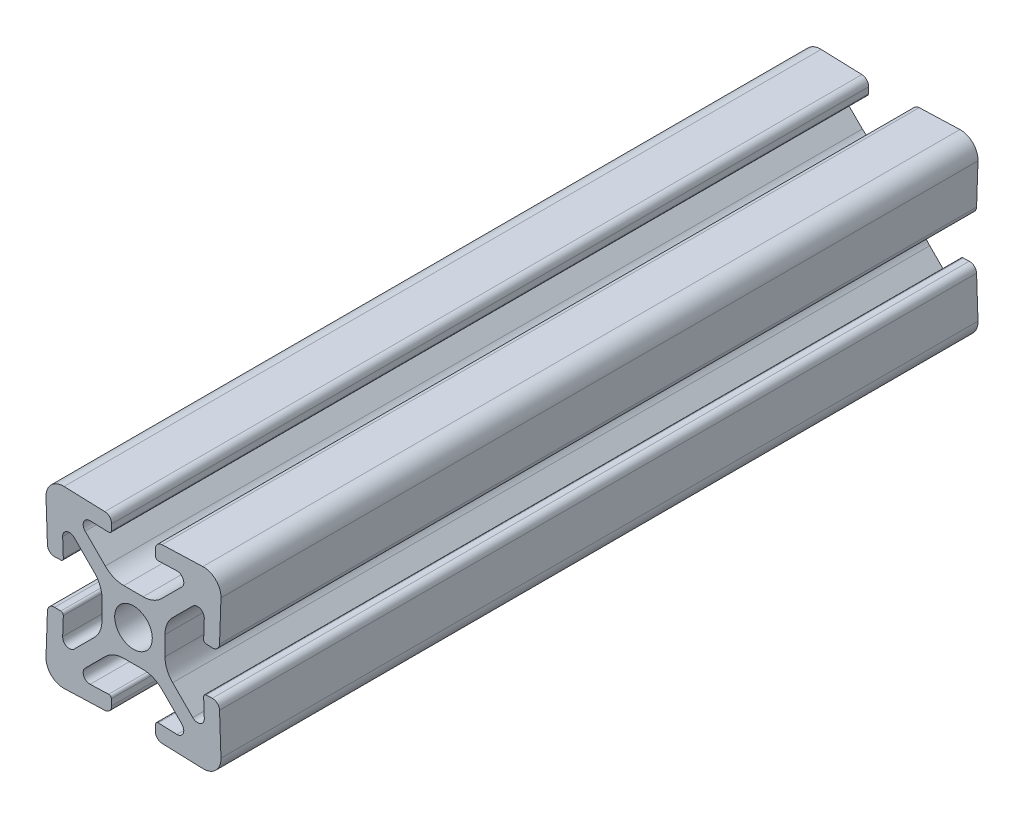
SolidWorks part; units mm, degrees
ref_plane "Front Plane" through (0, 0, 0) normal (0, 0, 1) x (1, 0, 0)
ref_plane "Top Plane" through (0, 0, 0) normal (0, 1, 0) x (1, 0, 0)
ref_plane "Right Plane" through (0, 0, 0) normal (1, 0, 0) x (0, 0, -1)
sketch "Sketch1" plane through (0, 0, 0) normal (0, 0, 1) x (1, 0, 0)
  line L0 (0, 0) -> (0, 10) construction
  line L1 (0, 0) -> (10, 0) construction
  line L2 (0, 0) -> (-10, 10) construction
  line L3 (-7.9302, 9.9988) -> (-3.2721, 9.8361)
  line L4 (-10, 10) -> (0, 10) construction
  line L6 (-2.8352, 8.0198) -> (-4.953, 8.0937)
  line L10 (0, 3.6) -> (-1.1022, 3.6)
  line L11 (-3.2236, 4.4787) -> (-5.5244, 6.7796)
  line L24 (0, 0) -> (-10, 0) construction
  line L25 (-10, 0) -> (0, 0) construction
  line L26 (0, 0) -> (0, -10) construction
  line L27 (-10, -10) -> (-10, 10) construction
  line L28 (0, 10) -> (10, 10) construction
  line L29 (-2.5249, 8.3091) -> (-2.5005, 9.0087)
  line L30 (-10, -10) -> (10, -10) construction
  arc A0 (-9.4142, 9.4142) -> (-7.9302, 9.9988) centre (-8, 8) cw
  arc A5 (-3.2721, 9.8361) -> (-2.5005, 9.0087) centre (-3.3, 9.0366) cw
  arc A6 (-1.1022, 3.6) -> (-3.2236, 4.4787) centre (-1.1022, 6.6) cw
  circle A16 centre (0, 0) radius 2.15
  arc A18 (-5.5244, 6.7796) -> (-4.953, 8.0937) centre (-4.9799, 7.3241) cw
  arc A20 (-2.8352, 8.0198) -> (-2.5249, 8.3091) centre (-2.8247, 8.3196) ccw
  point P15 (0, 0)
  point P42 (-2.3449, 3.6)
  point P80 (-10, 0)
  point P85 (0, -10)
  point P88 (0, -10)
  dimension "D11" = 2
  dimension "D15" = 3
  dimension "Center Hole Diameter" = 4.3
  dimension "D7" = 0.8
  dimension "D8" = 0.3
  dimension "D4" = 0.7701
  dimension "D1" = 45
  dimension "D2" = 2
  dimension "Rail Width" = 20
  dimension "T-Slot Depth" = 6.4
  dimension "D9" = 1.8
  dimension "Rail Height" = 20
  dimension "D23" = 7.2
  dimension "D5" = 11.5
  dimension "T-Slot Width" = 5
  dimension "D3" = 1.775
  dimension "D6" = 9.9598
sketch "Sketch2" plane through (0, 0, 0) normal (1, 0, 0) x (0, 0, -1)
  line L0 (-152.4, 0) -> (152.4, 0)
  line L1 (-152.4, -10) -> (-152.4, 10)
  line L2 (0, 0) -> (0, 10) construction
  line L3 (0, 0) -> (0, 10) construction
  line L4 (152.4, -10) -> (152.4, 10)
  point P0 (-122.4, 0)
  point P3 (0, 0)
  point P7 (122.4, 0)
  point P11 (-152.4, 0)
  point P14 (152.4, 0)
  dimension "D1" = 30
  dimension "Representative Length" = 304.8
sketch "Sketch3" plane through (0, 0, 0) normal (0, 0, 1) x (1, 0, 0)
  line L0 (-2.5249, 8.3091) -> (-2.5005, 9.0087) construction
  line L1 (0, 0) -> (-10, 10) construction
  line L2 (0, 0) -> (-10, 10) construction
  line L5 (-7.9302, 9.9988) -> (-3.2721, 9.8361) construction
  line L6 (-2.8352, 8.0198) -> (-4.953, 8.0937) construction
  line L17 (-2.5249, 8.3091) -> (-2.5005, 9.0087)
  line L19 (-2.8352, 8.0198) -> (-4.953, 8.0937)
  line L20 (0, 0) -> (0, 10) construction
  line L21 (-3.6, 0) -> (-2.15, 0)
  line L22 (-3.6, 0) -> (-3.6, 1.1022)
  line L23 (-4.4787, 3.2236) -> (-6.7796, 5.5244)
  line L42 (-3.2236, 4.4787) -> (-5.5244, 6.7796) construction
  line L43 (0, 3.6) -> (-1.1022, 3.6) construction
  line L44 (-7.9302, 9.9988) -> (-3.2721, 9.8361)
  line L47 (-3.2236, 4.4787) -> (-5.5244, 6.7796)
  line L48 (0, 3.6) -> (-1.1022, 3.6)
  line L59 (0, 3.6) -> (0, 2.15)
  line L60 (-9.9988, 7.9302) -> (-9.8361, 3.2721)
  line L61 (-8.0198, 2.8352) -> (-8.0937, 4.953)
  line L62 (-8.3091, 2.5249) -> (-9.0087, 2.5005)
  arc A0 (-7.9302, 9.9988) -> (-9.4142, 9.4142) centre (-8, 8) ccw construction
  arc A1 (-2.8352, 8.0198) -> (-2.5249, 8.3091) centre (-2.8247, 8.3196) ccw construction
  arc A3 (-2.8352, 8.0198) -> (-2.5249, 8.3091) centre (-2.8247, 8.3196) ccw
  arc A5 (-7.9302, 9.9988) -> (-9.9988, 7.9302) centre (-8, 8) ccw
  circle A13 centre (0, 0) radius 2.15 construction
  arc A14 (0, 2.15) -> (-2.15, 0) centre (0, 0) ccw
  arc A15 (-4.4787, 3.2236) -> (-3.6, 1.1022) centre (-6.6, 1.1022) cw
  arc A16 (-8.0937, 4.953) -> (-6.7796, 5.5244) centre (-7.3241, 4.9799) cw
  arc A17 (-9.0087, 2.5005) -> (-9.8361, 3.2721) centre (-9.0366, 3.3) cw
  arc A18 (-8.0198, 2.8352) -> (-8.3091, 2.5249) centre (-8.3196, 2.8247) cw
  arc A36 (-2.5005, 9.0087) -> (-3.2721, 9.8361) centre (-3.3, 9.0366) ccw construction
  arc A38 (-4.953, 8.0937) -> (-5.5244, 6.7796) centre (-4.9799, 7.3241) ccw construction
  arc A39 (-3.2236, 4.4787) -> (-1.1022, 3.6) centre (-1.1022, 6.6) ccw construction
  arc A41 (-2.5005, 9.0087) -> (-3.2721, 9.8361) centre (-3.3, 9.0366) ccw
  arc A43 (-4.953, 8.0937) -> (-5.5244, 6.7796) centre (-4.9799, 7.3241) ccw
  arc A44 (-3.2236, 4.4787) -> (-1.1022, 3.6) centre (-1.1022, 6.6) ccw
extrude "Boss-Extrude1" add sketch "Sketch3" along normal mid plane 86.53
pattern_circular "CirPattern1" count 4 over 360 about axis through (0, 0, 0) along (0, 0, 1) of "Boss-Extrude1"
ref_plane "Contact Plane 1" through (0, 10, 0) normal (0, 1, 0) x (1, 0, 0)
ref_plane "Contact Plane 2" through (10, 0, 0) normal (1, 0, 0) x (0, 0, -1)
ref_plane "Contact Plane 3" through (0, -10, 0) normal (0, -1, 0) x (-1, 0, 0)
ref_plane "Contact Plane 4" through (-10, 0, 0) normal (-1, 0, 0) x (0, 0, 1)
equation "\"D1@Sketch2\"=\"Rail Width@Sketch1\"*1.5"
equation "\"D1@Boss-Extrude1\" = \"Representative Length@Sketch2\""
